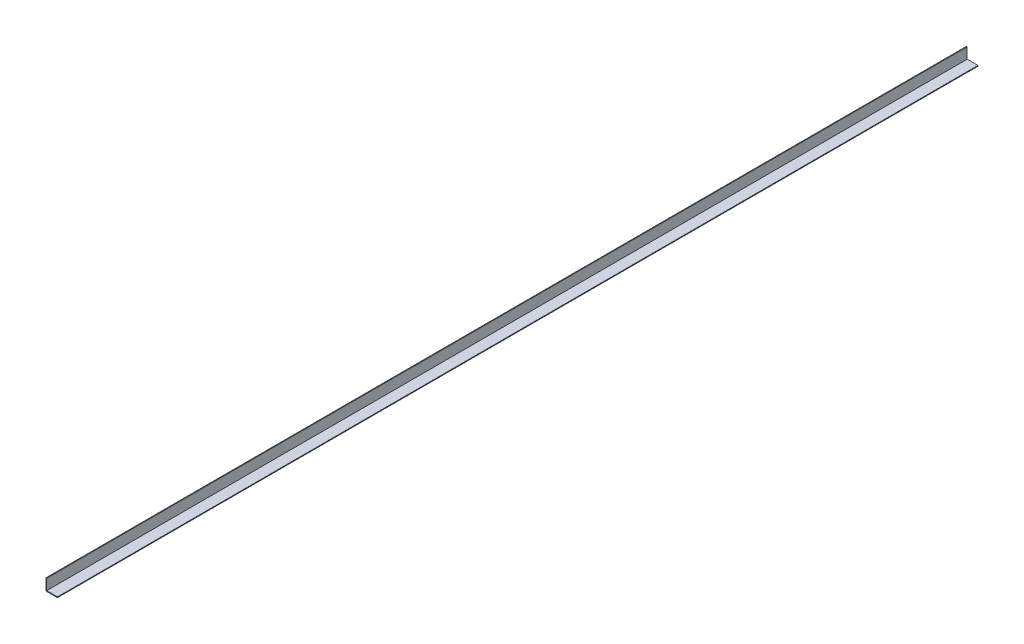
SolidWorks part; units mm, degrees
material "ASTM A36 Acero"
ref_plane "Alzado" through (0, 0, 0) normal (0, 0, 1) x (1, 0, 0)
ref_plane "Planta" through (0, 0, 0) normal (0, 1, 0) x (1, 0, 0)
ref_plane "Vista lateral" through (0, 0, 0) normal (1, 0, 0) x (0, 0, -1)
sketch "Croquis1" plane through (0, 0, 0) normal (0, 0, 1) x (1, 0, 0)
  line L0 (0, 76.2) -> (0, 0)
  line L1 (0, 0) -> (76.2, 0)
  line L2 (76.2, 0) -> (76.2, 4.76)
  line L3 (76.2, 4.76) -> (4.76, 4.76)
  line L4 (4.76, 4.76) -> (4.76, 76.2)
  line L5 (4.76, 76.2) -> (0, 76.2)
  dimension "D1" = 4.76
  dimension "D2" = 76.2
extrude "Saliente-Extruir1" add sketch "Croquis1" against normal blind 6100
